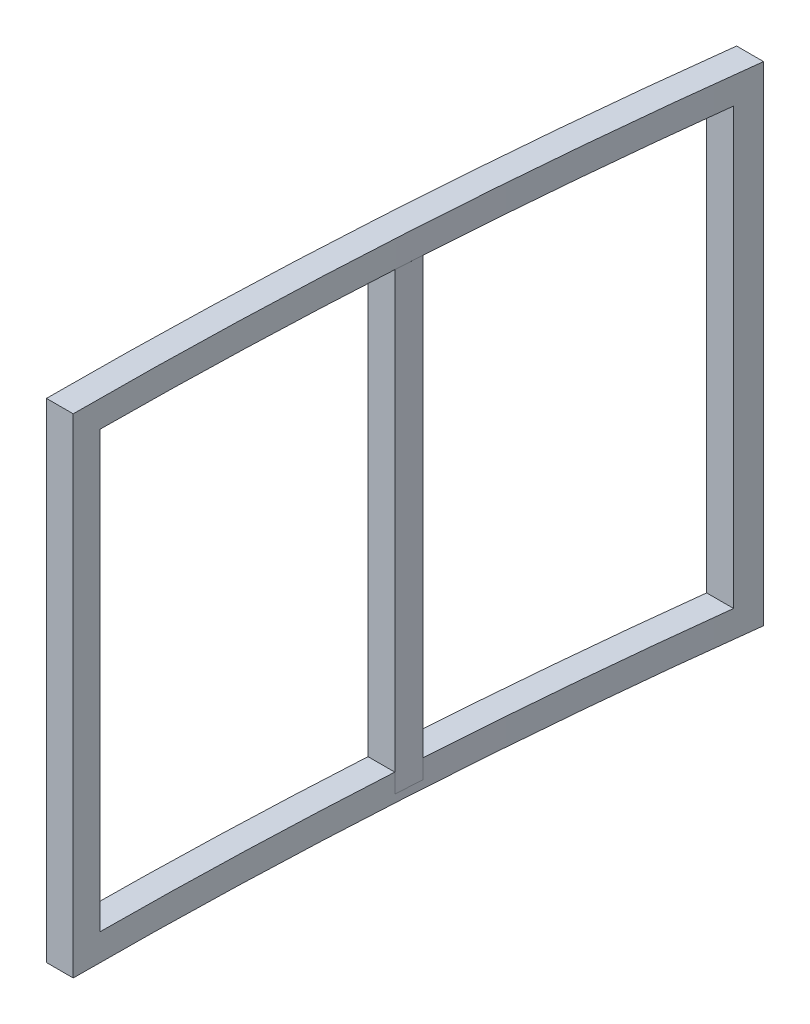
SolidWorks part; units mm, degrees
ref_plane "Front" through (0, 0, 0) normal (0, 0, 1) x (1, 0, 0)
ref_plane "Top" through (0, 0, 0) normal (0, 1, 0) x (1, 0, 0)
ref_plane "Right" through (0, 0, 0) normal (1, 0, 0) x (0, 0, -1)
sketch "Sketch1" plane through (0, 0, 0) normal (0, 1, 0) x (1, 0, 0)
  line L1 (-9820.6446, 1216.8845) -> (-9871.1258, 1216.8845)
  line L2 (-9895.75, 0) -> (-9945.85, 0)
  arc A0 (-9820.6446, 1216.8845) -> (-9895.75, 0) centre (0, 0) ccw
  arc A1 (-9871.1258, 1216.8845) -> (-9945.85, 0) centre (0, 0) ccw
  dimension "D1" = 19791.5
  dimension "D2" = 19891.7
  dimension "D3" = 1219.2
extrude "Boss-Extrude1" add sketch "Sketch1" along normal blind 914.4
ref_plane "Plane1" through (9945.85, 0, 0) normal (1, 0, 0) x (0, 0, -1)
sketch "Sketch2" plane through (9945.85, 0, 0) normal (1, 0, 0) x (0, 0, -1)
  line L1 (0, 0) -> (1216.8845, 0) construction
  line L2 (0, 0) -> (0, 914.4) construction
  line L3 (0, 914.4) -> (1216.8845, 914.4) construction
  line L4 (1216.8845, 0) -> (1216.8845, 914.4) construction
  line L5 (1166.8845, 864.4) -> (50, 864.4)
  line L6 (1166.8845, 864.4) -> (1166.8845, 50)
  line L7 (1166.8845, 50) -> (50, 50)
  line L8 (50, 864.4) -> (50, 50)
  line L9 (1166.8845, 864.4) -> (50, 50) construction
  line L10 (1166.8845, 50) -> (50, 864.4) construction
  point P6 (608.4422, 457.2)
  dimension "D1" = 50
  dimension "D2" = 50
  dimension "D3" = 50
  dimension "D4" = 50
extrude "Cut-Extrude1" cut sketch "Sketch2" against normal through all
sketch "Sketch5" plane through (0, 864.4, 0) normal (0, -1, 0) x (1, 0, 0)
  line L0 (-9925.5839, -634.6) -> (-9875.3811, -634.6)
  line L1 (-9928.6542, -584.6) -> (-9878.467, -584.6)
  line L2 (-9895.75, 0) -> (-9820.6446, -1216.8845) construction
  line L3 (-9928.6542, -584.6) -> (-9925.5839, -634.6)
  line L4 (-9878.467, -584.6) -> (-9875.3811, -634.6)
  arc A0 (-9945.85, 0) -> (-9871.1258, -1216.8845) centre (0, 0) ccw construction
  arc A1 (-9895.75, 0) -> (-9820.6446, -1216.8845) centre (0, 0) ccw construction
  dimension "D1" = 50
  dimension "D2" = 584.6
extrude "Boss-Extrude3" add sketch "Sketch5" along normal blind 850
equation "\"inside\" = 9895.75 * 2"
equation "\"D1@Sketch1\"=\"inside\""
equation "\"outside\" = 9945.85 * 2"
equation "\"D2@Sketch1\"=\"outside\""
equation "\"cut\"=1219.2"
equation "\"centeringline\"=584.6"
equation "\"D2@Sketch5\"=\"centeringline\""
equation "\"framewidth\"=50"
equation "\"D1@Sketch5\"=\"framewidth\""
